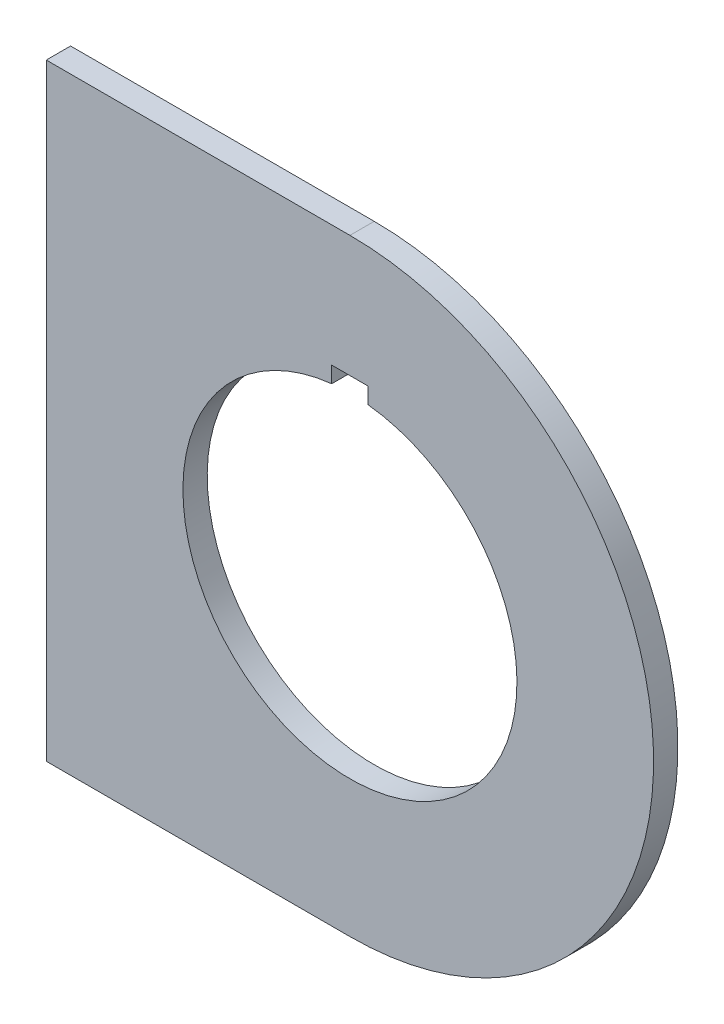
SolidWorks part; units mm, degrees
ref_plane "Face" through (0, 0, 0) normal (0, 0, 1) x (1, 0, 0)
ref_plane "Dessus" through (0, 0, 0) normal (0, 1, 0) x (1, 0, 0)
ref_plane "Droite" through (0, 0, 0) normal (1, 0, 0) x (0, 0, -1)
sketch "Esquisse1" plane through (0, 0, 0) normal (0, 0, 1) x (1, 0, 0)
  line L0 (23.5, 40) -> (23.5, 38.6679)
  line L1 (0, 0) -> (25, 0)
  line L2 (0, 0) -> (0, 50)
  line L3 (0, 50) -> (25, 50)
  line L4 (26.5, 40) -> (26.5, 38.6679)
  line L5 (23.5, 40) -> (26.5, 40)
  arc A0 (25, 0) -> (25, 50) centre (25, 25) ccw
  arc A1 (23.5, 38.6679) -> (26.5, 38.6679) centre (25, 25) ccw
  dimension "D2" = 25
  dimension "D3" = 25
  dimension "D4" = 27.5
  dimension "D1" = 50
  dimension "D5" = 1.5
  dimension "D6" = 1.5
  dimension "D7" = 15
extrude "Boss.-Extru.1" add sketch "Esquisse1" along normal blind 2
